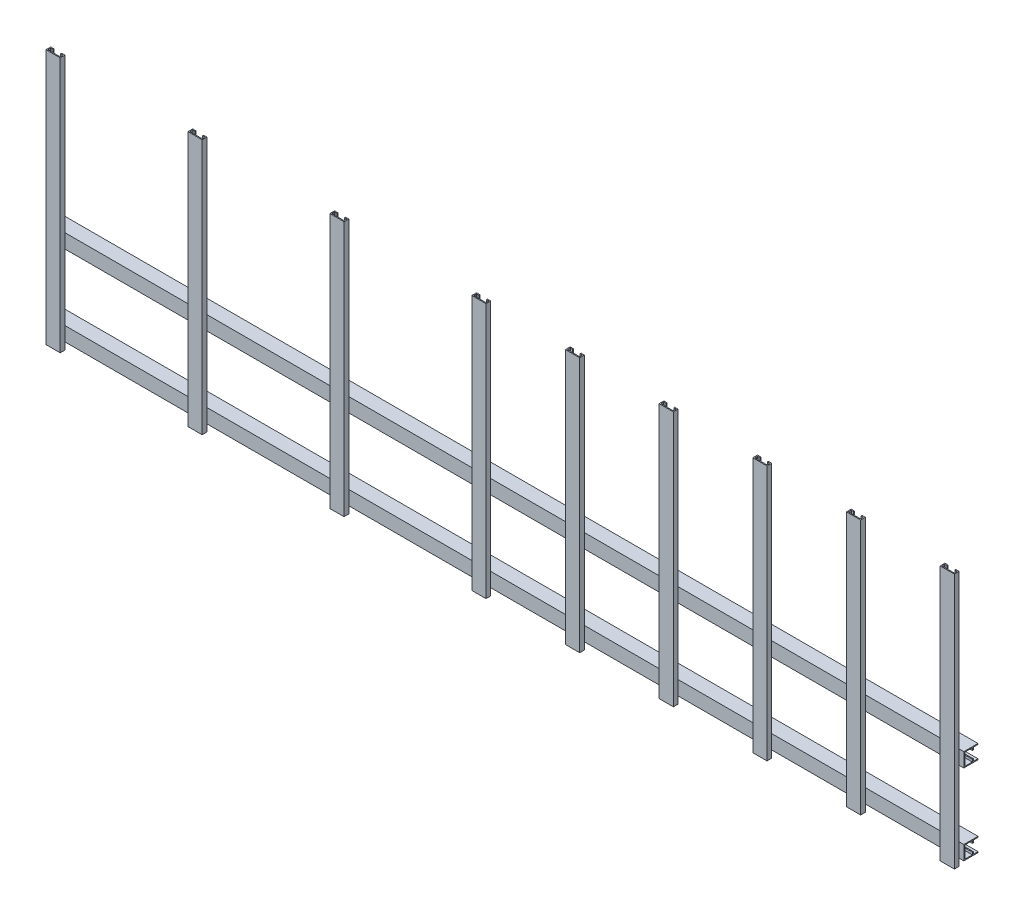
SolidWorks part; units mm, degrees
ref_plane "Front Plane" through (0, 0, 0) normal (0, 0, 1) x (1, 0, 0)
ref_plane "Top Plane" through (0, 0, 0) normal (0, 1, 0) x (1, 0, 0)
ref_plane "Right Plane" through (0, 0, 0) normal (1, 0, 0) x (0, 0, -1)
sketch "Sketch1" plane through (0, 0, 0) normal (0, 0, 1) x (1, 0, 0)
  line L1 (-485, 0) -> (485, 0)
  line L2 (-485, 0) -> (-485, -15)
  line L3 (-485, -15) -> (485, -15)
  line L4 (485, 0) -> (485, -15)
  line L5 (-485, -85) -> (485, -85)
  line L6 (-485, -85) -> (-485, -100)
  line L7 (-485, -100) -> (485, -100)
  line L8 (485, -85) -> (485, -100)
  point P8 (0, 0)
  dimension "D1" = 970
  dimension "D2" = 15
  dimension "D3" = 100
extrude "Boss-Extrude1" add sketch "Sketch1" along normal blind 15
sketch "Sketch2" plane through (0, 0, 15) normal (0, 0, 1) x (1, 0, 0)
  line L0 (485, -15) -> (485, 0) construction
  line L1 (480, 162.5) -> (465, 162.5)
  line L2 (480, 162.5) -> (480, -107.5)
  line L3 (480, -107.5) -> (465, -107.5)
  line L4 (465, 162.5) -> (465, -107.5)
  line L5 (-485, -100) -> (485, -100) construction
  line L10 (381, 162.5) -> (366, 162.5)
  line L11 (366, 162.5) -> (366, -107.5)
  line L12 (381, 162.5) -> (381, -107.5)
  line L13 (381, -107.5) -> (366, -107.5)
  line L14 (282, 162.5) -> (267, 162.5)
  line L15 (267, 162.5) -> (267, -107.5)
  line L16 (282, 162.5) -> (282, -107.5)
  line L17 (282, -107.5) -> (267, -107.5)
  line L18 (183, 162.5) -> (168, 162.5)
  line L19 (168, 162.5) -> (168, -107.5)
  line L20 (183, 162.5) -> (183, -107.5)
  line L21 (183, -107.5) -> (168, -107.5)
  line L22 (84, 162.5) -> (69, 162.5)
  line L23 (69, 162.5) -> (69, -107.5)
  line L24 (84, 162.5) -> (84, -107.5)
  line L25 (84, -107.5) -> (69, -107.5)
  line L26 (-15, 162.5) -> (-30, 162.5)
  line L27 (-30, 162.5) -> (-30, -107.5)
  line L28 (-15, 162.5) -> (-15, -107.5)
  line L29 (-15, -107.5) -> (-30, -107.5)
  line L30 (-480, 162.5) -> (-480, -107.5)
  line L31 (-465, 162.5) -> (-465, -107.5)
  line L32 (-480, 162.5) -> (-465, 162.5)
  line L33 (-465, -107.5) -> (-480, -107.5)
  line L34 (-485, 0) -> (-485, -15) construction
  line L35 (-315, -107.5) -> (-330, -107.5)
  line L36 (-330, 162.5) -> (-330, -107.5)
  line L37 (-330, 162.5) -> (-315, 162.5)
  line L38 (-315, 162.5) -> (-315, -107.5)
  line L39 (-165, -107.5) -> (-180, -107.5)
  line L40 (-180, 162.5) -> (-180, -107.5)
  line L41 (-180, 162.5) -> (-165, 162.5)
  line L42 (-165, 162.5) -> (-165, -107.5)
  dimension "D1" = 270
  dimension "D2" = 15
  dimension "D3" = 5
  dimension "D4" = 7.5
  dimension "D5" = 6
  dimension "D6" = 84
  dimension "D7" = 5
  dimension "D8" = 15
  dimension "D9" = 270
  dimension "D10" = 7.5
  dimension "D12" = 135
  dimension "D11" = 3
extrude "Boss-Extrude2" add sketch "Sketch2" along normal blind 5
sketch "Sketch3" plane through (0, 162.5, 0) normal (0, 1, 0) x (1, 0, 0)
  line L0 (466.5, -19) -> (478.5, -19)
  line L1 (466, -16.5) -> (466, -18.5)
  line L2 (479, -18.5) -> (479, -16.5)
  line L3 (465, -20) -> (465, -15) construction
  line L4 (480, -20) -> (480, -15) construction
  line L5 (480, -20) -> (465, -20) construction
  line L6 (466.5, -16) -> (468.5, -16)
  line L7 (476.5, -16) -> (478.5, -16)
  line L8 (480, -15) -> (465, -15) construction
  line L9 (468.5, -16) -> (468.5, -15)
  line L10 (476.5, -16) -> (476.5, -15)
  line L11 (468.5, -15) -> (476.5, -15)
  line L12 (380, -18.5) -> (380, -16.5)
  line L13 (377.5, -16) -> (379.5, -16)
  line L14 (377.5, -16) -> (377.5, -15)
  line L15 (369.5, -15) -> (377.5, -15)
  line L16 (369.5, -16) -> (369.5, -15)
  line L17 (367.5, -16) -> (369.5, -16)
  line L18 (367, -16.5) -> (367, -18.5)
  line L19 (367.5, -19) -> (379.5, -19)
  line L20 (281, -18.5) -> (281, -16.5)
  line L21 (278.5, -16) -> (280.5, -16)
  line L22 (278.5, -16) -> (278.5, -15)
  line L23 (270.5, -15) -> (278.5, -15)
  line L24 (270.5, -16) -> (270.5, -15)
  line L25 (268.5, -16) -> (270.5, -16)
  line L26 (268, -16.5) -> (268, -18.5)
  line L27 (268.5, -19) -> (280.5, -19)
  line L28 (182, -18.5) -> (182, -16.5)
  line L29 (179.5, -16) -> (181.5, -16)
  line L30 (179.5, -16) -> (179.5, -15)
  line L31 (171.5, -15) -> (179.5, -15)
  line L32 (171.5, -16) -> (171.5, -15)
  line L33 (169.5, -16) -> (171.5, -16)
  line L34 (169, -16.5) -> (169, -18.5)
  line L35 (169.5, -19) -> (181.5, -19)
  line L36 (83, -18.5) -> (83, -16.5)
  line L37 (80.5, -16) -> (82.5, -16)
  line L38 (80.5, -16) -> (80.5, -15)
  line L39 (72.5, -15) -> (80.5, -15)
  line L40 (72.5, -16) -> (72.5, -15)
  line L41 (70.5, -16) -> (72.5, -16)
  line L42 (70, -16.5) -> (70, -18.5)
  line L43 (70.5, -19) -> (82.5, -19)
  line L44 (-16, -18.5) -> (-16, -16.5)
  line L45 (-18.5, -16) -> (-16.5, -16)
  line L46 (-18.5, -16) -> (-18.5, -15)
  line L47 (-26.5, -15) -> (-18.5, -15)
  line L48 (-26.5, -16) -> (-26.5, -15)
  line L49 (-28.5, -16) -> (-26.5, -16)
  line L50 (-29, -16.5) -> (-29, -18.5)
  line L51 (-28.5, -19) -> (-16.5, -19)
  line L52 (-466, -18.5) -> (-466, -16.5)
  line L53 (-468.5, -16) -> (-466.5, -16)
  line L54 (-468.5, -16) -> (-468.5, -15)
  line L55 (-476.5, -15) -> (-468.5, -15)
  line L56 (-476.5, -16) -> (-476.5, -15)
  line L57 (-478.5, -16) -> (-476.5, -16)
  line L58 (-479, -16.5) -> (-479, -18.5)
  line L59 (-478.5, -19) -> (-466.5, -19)
  line L60 (-316, -18.5) -> (-316, -16.5)
  line L61 (-318.5, -16) -> (-316.5, -16)
  line L62 (-318.5, -16) -> (-318.5, -15)
  line L63 (-326.5, -15) -> (-318.5, -15)
  line L64 (-326.5, -16) -> (-326.5, -15)
  line L65 (-328.5, -16) -> (-326.5, -16)
  line L66 (-329, -16.5) -> (-329, -18.5)
  line L67 (-328.5, -19) -> (-316.5, -19)
  line L68 (-166, -18.5) -> (-166, -16.5)
  line L69 (-168.5, -16) -> (-166.5, -16)
  line L70 (-168.5, -16) -> (-168.5, -15)
  line L71 (-176.5, -15) -> (-168.5, -15)
  line L72 (-176.5, -16) -> (-176.5, -15)
  line L73 (-178.5, -16) -> (-176.5, -16)
  line L74 (-179, -16.5) -> (-179, -18.5)
  line L75 (-178.5, -19) -> (-166.5, -19)
  arc A0 (479, -16.5) -> (478.5, -16) centre (478.5, -16.5) ccw
  arc A1 (466.5, -16) -> (466, -16.5) centre (466.5, -16.5) ccw
  arc A2 (478.5, -19) -> (479, -18.5) centre (478.5, -18.5) ccw
  arc A3 (466, -18.5) -> (466.5, -19) centre (466.5, -18.5) ccw
  arc A4 (466, -16.5) -> (466.5, -16) centre (466.5, -16.5) ccw construction
  arc A5 (466.5, -19) -> (466, -18.5) centre (466.5, -18.5) ccw construction
  arc A6 (478.5, -16) -> (479, -16.5) centre (478.5, -16.5) ccw construction
  arc A7 (479, -18.5) -> (478.5, -19) centre (478.5, -18.5) ccw construction
  arc A8 (379.5, -19) -> (380, -18.5) centre (379.5, -18.5) ccw
  arc A9 (380, -16.5) -> (379.5, -16) centre (379.5, -16.5) ccw
  arc A10 (367.5, -16) -> (367, -16.5) centre (367.5, -16.5) ccw
  arc A11 (367, -18.5) -> (367.5, -19) centre (367.5, -18.5) ccw
  arc A12 (280.5, -19) -> (281, -18.5) centre (280.5, -18.5) ccw
  arc A13 (281, -16.5) -> (280.5, -16) centre (280.5, -16.5) ccw
  arc A14 (268.5, -16) -> (268, -16.5) centre (268.5, -16.5) ccw
  arc A15 (268, -18.5) -> (268.5, -19) centre (268.5, -18.5) ccw
  arc A16 (181.5, -19) -> (182, -18.5) centre (181.5, -18.5) ccw
  arc A17 (182, -16.5) -> (181.5, -16) centre (181.5, -16.5) ccw
  arc A18 (169.5, -16) -> (169, -16.5) centre (169.5, -16.5) ccw
  arc A19 (169, -18.5) -> (169.5, -19) centre (169.5, -18.5) ccw
  arc A20 (82.5, -19) -> (83, -18.5) centre (82.5, -18.5) ccw
  arc A21 (83, -16.5) -> (82.5, -16) centre (82.5, -16.5) ccw
  arc A22 (70.5, -16) -> (70, -16.5) centre (70.5, -16.5) ccw
  arc A23 (70, -18.5) -> (70.5, -19) centre (70.5, -18.5) ccw
  arc A24 (-16.5, -19) -> (-16, -18.5) centre (-16.5, -18.5) ccw
  arc A25 (-16, -16.5) -> (-16.5, -16) centre (-16.5, -16.5) ccw
  arc A26 (-28.5, -16) -> (-29, -16.5) centre (-28.5, -16.5) ccw
  arc A27 (-29, -18.5) -> (-28.5, -19) centre (-28.5, -18.5) ccw
  arc A28 (-466.5, -19) -> (-466, -18.5) centre (-466.5, -18.5) ccw
  arc A29 (-466, -16.5) -> (-466.5, -16) centre (-466.5, -16.5) ccw
  arc A30 (-478.5, -16) -> (-479, -16.5) centre (-478.5, -16.5) ccw
  arc A31 (-479, -18.5) -> (-478.5, -19) centre (-478.5, -18.5) ccw
  arc A32 (-316, -16.5) -> (-316.5, -16) centre (-316.5, -16.5) ccw
  arc A33 (-328.5, -16) -> (-329, -16.5) centre (-328.5, -16.5) ccw
  arc A34 (-329, -18.5) -> (-328.5, -19) centre (-328.5, -18.5) ccw
  arc A35 (-316.5, -19) -> (-316, -18.5) centre (-316.5, -18.5) ccw
  arc A36 (-166, -16.5) -> (-166.5, -16) centre (-166.5, -16.5) ccw
  arc A37 (-178.5, -16) -> (-179, -16.5) centre (-178.5, -16.5) ccw
  arc A38 (-179, -18.5) -> (-178.5, -19) centre (-178.5, -18.5) ccw
  arc A39 (-166.5, -19) -> (-166, -18.5) centre (-166.5, -18.5) ccw
  point P3 (-468.5, -15.5)
  dimension "D5" = 1
  dimension "D6" = 2
  dimension "D7" = 6
  dimension "D1" = 1
  dimension "D2" = 1
  dimension "D3" = 1
  dimension "D4" = 1
  dimension "D8" = 99
  dimension "D10" = 945
  dimension "D12" = 150
  dimension "D9" = 2
  dimension "D11" = 3
extrude "Cut-Extrude1" cut sketch "Sketch3" against normal through all
sketch "Sketch4" plane through (-485, 0, 0) normal (-1, 0, 0) x (0, 0, 1)
  line L0 (14, -1) -> (14, -14)
  line L1 (14, -1) -> (6, -1)
  line L2 (14, -14) -> (6, -14)
  line L3 (0, -1) -> (5, -1)
  line L4 (0, 0) -> (0, -15) construction
  line L5 (0, -14) -> (5, -14)
  line L6 (5, -14) -> (5, -11.5)
  line L7 (6, -11.5) -> (5, -11.5)
  line L8 (6, -11.5) -> (6, -14)
  line L9 (6, -1) -> (6, -3.5)
  line L10 (6, -3.5) -> (5, -3.5)
  line L11 (5, -3.5) -> (5, -1)
  line L12 (15, 0) -> (0, 0) construction
  line L13 (15, 0) -> (15, -15) construction
  line L14 (15, -15) -> (0, -15) construction
  line L15 (0, -1) -> (0, -14)
  line L16 (0, -86) -> (0, -99)
  line L17 (0, -99) -> (5, -99)
  line L18 (5, -99) -> (5, -96.5)
  line L19 (6, -96.5) -> (5, -96.5)
  line L20 (6, -96.5) -> (6, -99)
  line L21 (14, -99) -> (6, -99)
  line L22 (14, -86) -> (14, -99)
  line L23 (14, -86) -> (6, -86)
  line L24 (6, -86) -> (6, -88.5)
  line L25 (6, -88.5) -> (5, -88.5)
  line L26 (5, -88.5) -> (5, -86)
  line L27 (0, -86) -> (5, -86)
  dimension "D1" = 1
  dimension "D2" = 1
  dimension "D3" = 1
  dimension "D4" = 1
  dimension "D5" = 2.5
  dimension "D6" = 8
  dimension "D8" = 85
  dimension "D7" = 2
extrude "Cut-Extrude2" cut sketch "Sketch4" against normal through all
